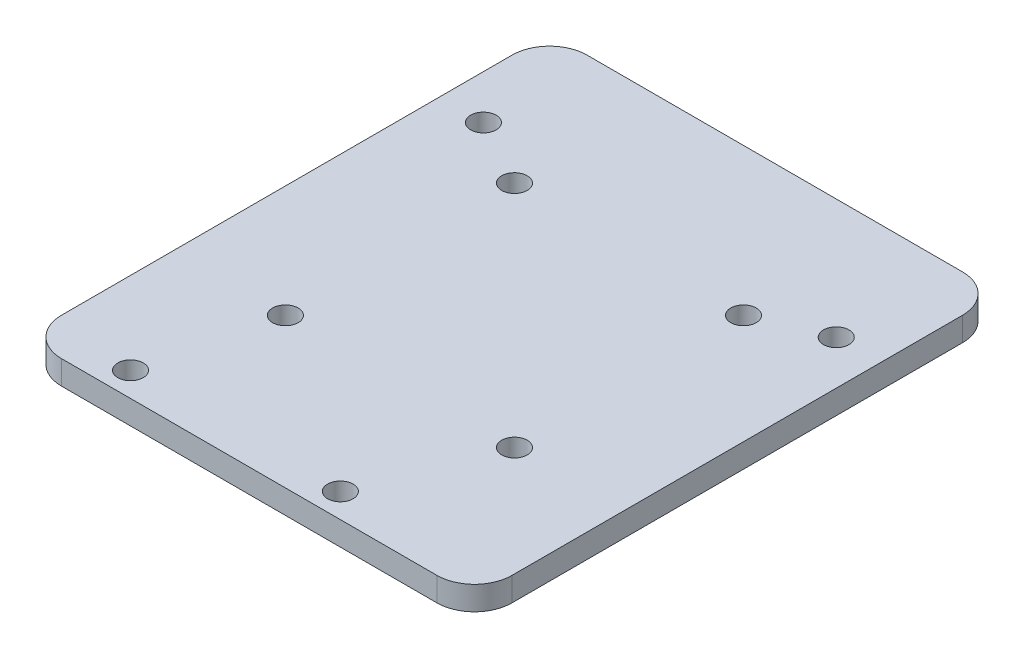
SolidWorks part; units mm, degrees
ref_plane "Front Plane" through (0, 0, 0) normal (0, 0, 1) x (1, 0, 0)
ref_plane "Top Plane" through (0, 0, 0) normal (0, 1, 0) x (1, 0, 0)
ref_plane "Right Plane" through (0, 0, 0) normal (1, 0, 0) x (0, 0, -1)
sketch "Sketch1" plane through (0, 0, 0) normal (0, 1, 0) x (1, 0, 0)
  line L1 (30, -35) -> (-30, -35)
  line L2 (30, -35) -> (30, 35)
  line L3 (30, 35) -> (-30, 35)
  line L4 (-30, -35) -> (-30, 35)
  line L5 (30, -35) -> (-30, 35) construction
  line L6 (30, 35) -> (-30, -35) construction
  point P0 (0, 0)
  dimension "D1" = 60
  dimension "D2" = 70
extrude "Boss-Extrude1" add sketch "Sketch1" along normal blind 3.175
hole_wizard "M3 Clearance Hole1" positions "Sketch3" profile "Sketch2" hole size "M3" standard "ANSI Metric" end condition through all
sketch "Sketch3" plane through (0, 3.175, 0) normal (0, 1, 0) x (1, 0, 0)
  point P0 (15.4254, 15.4017)
  point P3 (15.4254, -15.0983)
  point P6 (-15.0746, -15.0983)
  point P9 (-15.0746, 15.4017)
sketch "Sketch2" plane through (15.4254, 3.175, -15.4017) normal (1, 0, 0) x (0, 0, 1)
  line L0 (0, 0) -> (0, 3.175)
  line L1 (0, 3.175) -> (1.7, 3.175)
  line L2 (1.7, 3.175) -> (1.7, 0)
  line L5 (1.7, 0) -> (0, 0)
  line L11 (0, -6.35) -> (0, 107.95) construction
  dimension "Thru Hole Dia." = 3.4
  dimension "Thru Hole Depth" = 3.175
hole_wizard "M3 Clearance Hole2" positions "Sketch5" profile "Sketch4" hole size "M3" standard "ANSI Metric" end condition through all
sketch "Sketch5" plane through (0, 3.175, 0) normal (0, 1, 0) x (1, 0, 0)
  point P0 (-19.05, -31.75)
  point P3 (8.89, -31.75)
  point P6 (24.13, 19.05)
  point P9 (-24.13, 20.32)
sketch "Sketch4" plane through (-19.05, 3.175, 31.75) normal (1, 0, 0) x (0, 0, 1)
  line L0 (0, 0) -> (0, 3.175)
  line L1 (0, 3.175) -> (1.7, 3.175)
  line L2 (1.7, 3.175) -> (1.7, 0)
  line L5 (1.7, 0) -> (0, 0)
  line L11 (0, -6.35) -> (0, 107.95) construction
  dimension "Thru Hole Dia." = 3.4
  dimension "Thru Hole Depth" = 3.175
fillet "Fillet1" radius 5 4 edges at (-30, 1.5875, -35) (30, 1.5875, -35) (30, 1.5875, 35) (-30, 1.5875, 35)
